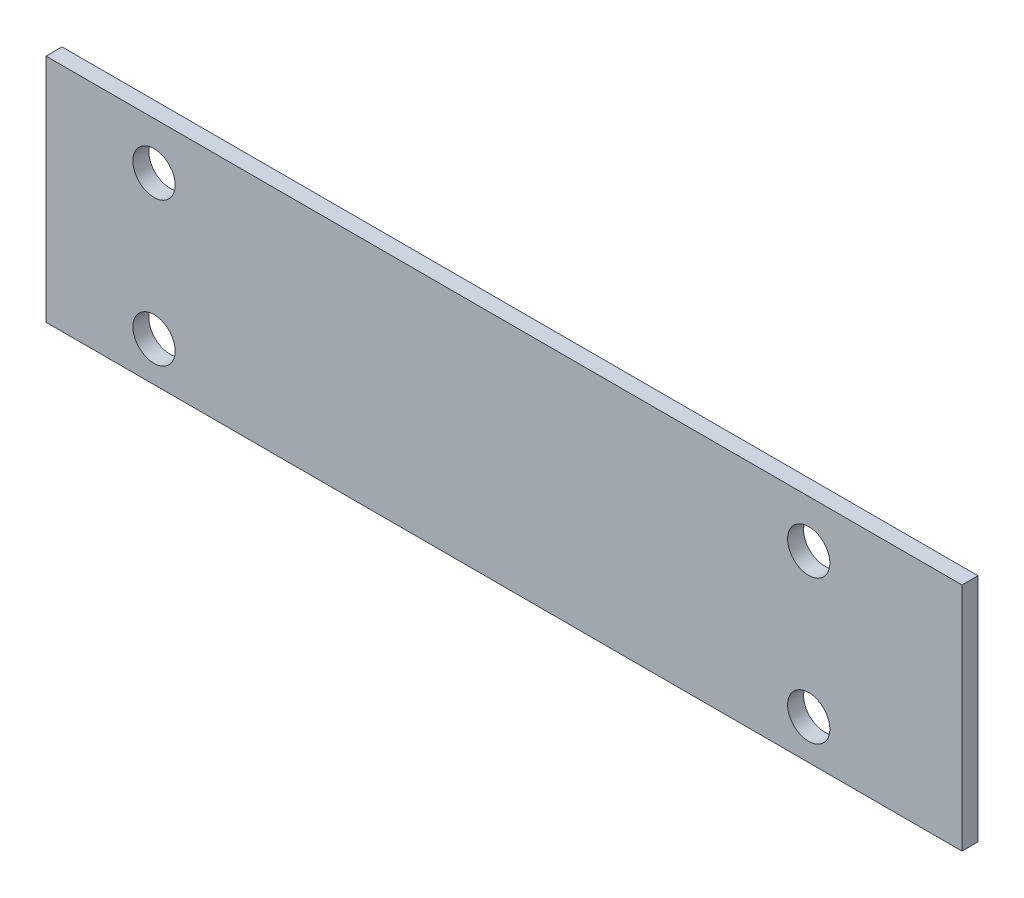
SolidWorks part; units mm, degrees
ref_plane "Front Plane" through (0, 0, 0) normal (0, 0, 1) x (1, 0, 0)
ref_plane "Top Plane" through (0, 0, 0) normal (0, 1, 0) x (1, 0, 0)
ref_plane "Right Plane" through (0, 0, 0) normal (1, 0, 0) x (0, 0, -1)
sketch "Sketch1" plane through (0, 0, 0) normal (0, 0, 1) x (1, 0, 0)
  line L1 (0, 0) -> (-119.19, 0)
  line L2 (0, 0) -> (0, 30)
  line L3 (0, 30) -> (-119.19, 30)
  line L4 (-119.19, 0) -> (-119.19, 30)
  arc A2 (0, 23.8544) -> (0, 26.1456) centre (-2.5, 25) ccw
  arc A3 (0, 3.8544) -> (0, 6.1456) centre (-2.5, 5) ccw
  circle A6 centre (-105.1329, 23.85) radius 2.75
  circle A7 centre (-105.1329, 5.15) radius 2.75
  circle A8 centre (-19.9467, 23.85) radius 2.75
  circle A9 centre (-19.9467, 5.15) radius 2.75
  dimension "D1" = 30
  dimension "D2" = 119.19
extrude "Boss-Extrude1" add sketch "Sketch1" along normal mid plane 2.08
